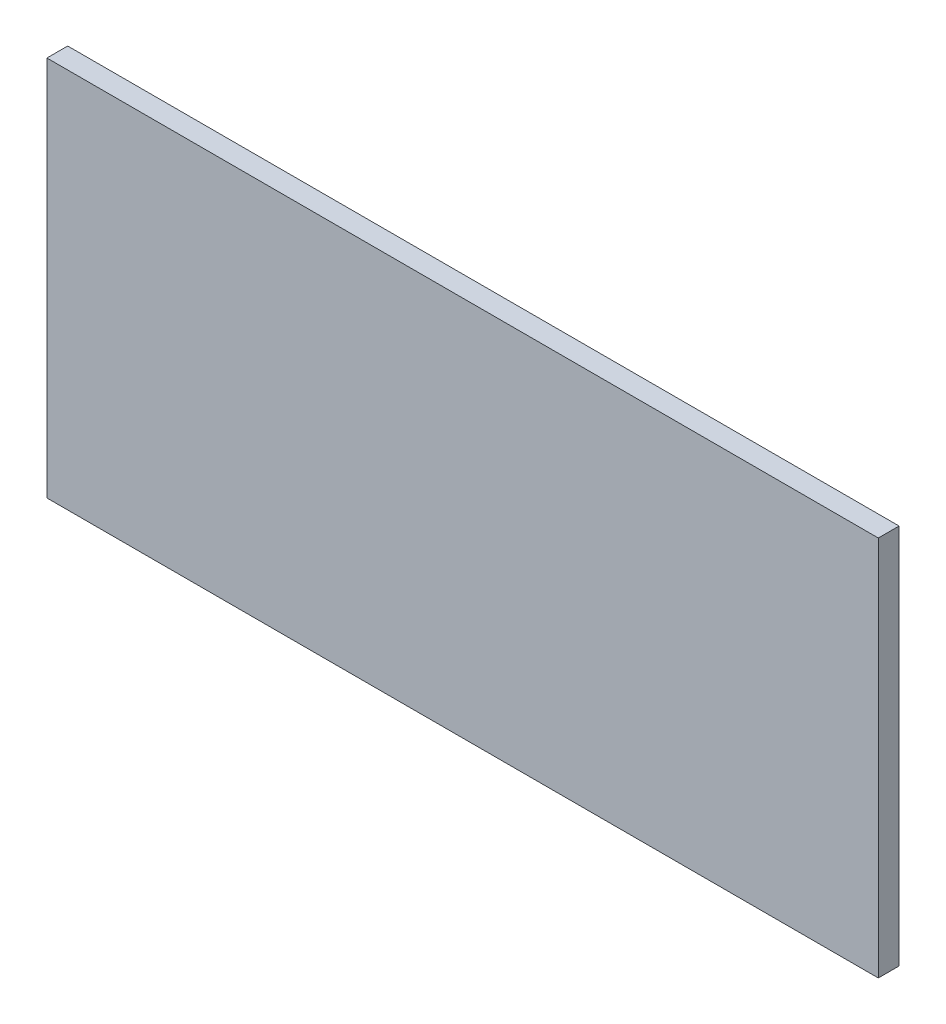
SolidWorks part; units mm, degrees
material "Acrylic (Medium-high impact)"
ref_plane "Front Plane" through (0, 0, 0) normal (0, 0, 1) x (1, 0, 0)
ref_plane "Top Plane" through (0, 0, 0) normal (0, 1, 0) x (1, 0, 0)
ref_plane "Right Plane" through (0, 0, 0) normal (1, 0, 0) x (0, 0, -1)
sketch "Sketch1" plane through (0, 0, 0) normal (0, 0, 1) x (1, 0, 0)
  line L1 (0, 0) -> (120, 0)
  line L2 (0, 0) -> (0, 55)
  line L3 (0, 55) -> (120, 55)
  line L4 (120, 0) -> (120, 55)
  dimension "D1" = 120
  dimension "D2" = 55
extrude "Boss-Extrude1" add sketch "Sketch1" against normal blind 3
